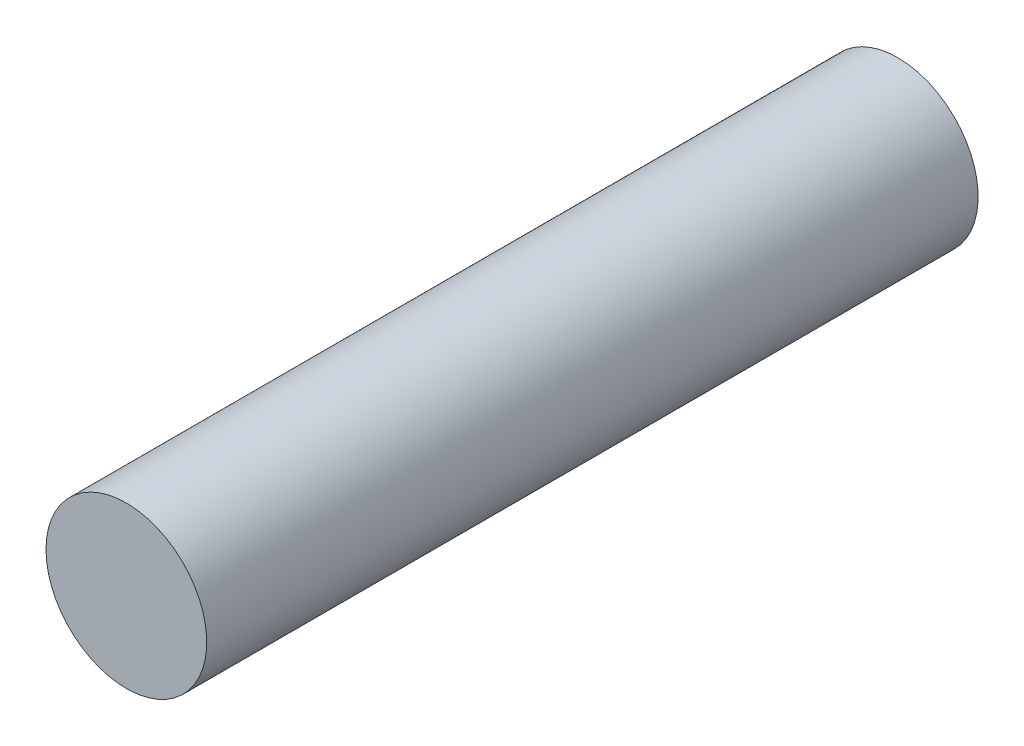
SolidWorks part; units mm, degrees
material "Pine"
ref_plane "Front Plane" through (0, 0, 0) normal (0, 0, 1) x (1, 0, 0)
ref_plane "Top Plane" through (0, 0, 0) normal (0, 1, 0) x (1, 0, 0)
ref_plane "Right Plane" through (0, 0, 0) normal (1, 0, 0) x (0, 0, -1)
sketch "Sketch1" plane through (0, 0, 0) normal (0, 0, 1) x (1, 0, 0)
  circle A0 centre (0, 0) radius 7.9375
  dimension "D1" = 15.875
extrude "Boss-Extrude1" add sketch "Sketch1" along normal blind 76.2
